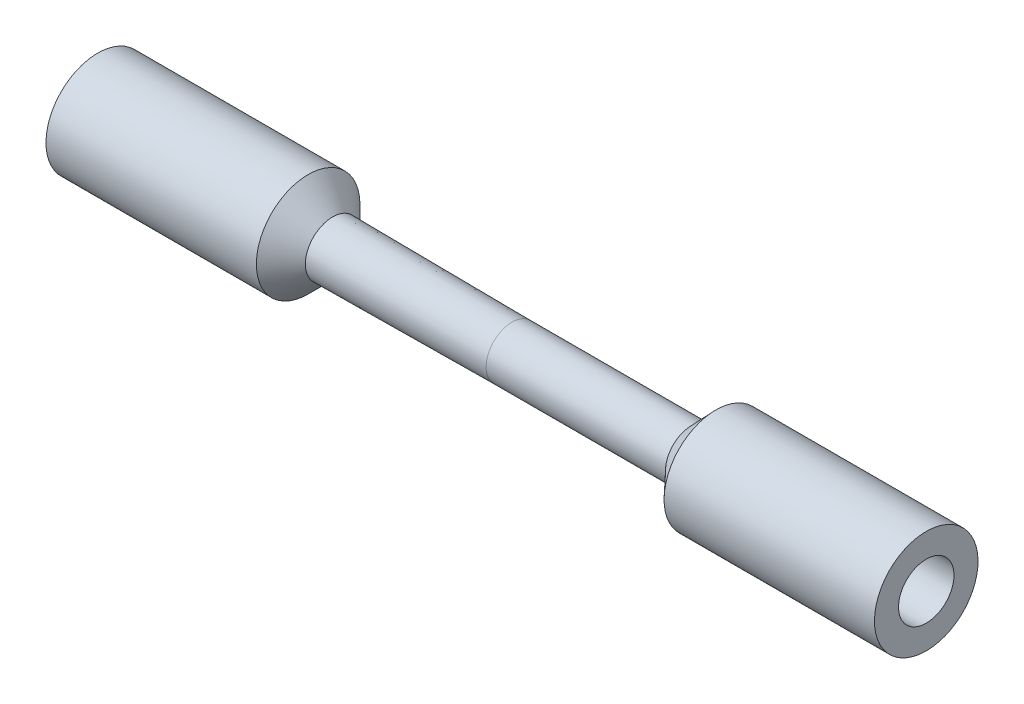
SolidWorks part; units mm, degrees
ref_plane "Front Plane" through (0, 0, 0) normal (0, 0, 1) x (1, 0, 0)
ref_plane "Top Plane" through (0, 0, 0) normal (0, 1, 0) x (1, 0, 0)
ref_plane "Right Plane" through (0, 0, 0) normal (1, 0, 0) x (0, 0, -1)
sketch "Sketch1" plane through (0, 0, 0) normal (0, 0, 1) x (1, 0, 0)
  line L0 (25.4, 1.5875) -> (14.4003, 1.5)
  line L1 (0, 0) -> (50.8, 0) construction
  line L2 (0, 0) -> (0, 3.175)
  line L3 (0, 3.175) -> (50.8, 3.175)
  line L4 (50.8, 0) -> (50.8, 3.175)
  line L5 (25.4, 3.175) -> (25.4, 0) construction
  line L6 (14.4003, 1.5) -> (12.9003, 0)
  line L7 (12.9003, 0) -> (0, 0)
  line L8 (37.8997, 0) -> (50.8, 0)
  line L9 (25.4, 1.5875) -> (36.4, 1.5875)
  line L10 (36.4, 1.5875) -> (37.8997, 0)
  point P208 (25.4, 1.5)
  dimension "D1" = 50.8
  dimension "D2" = 3.175
  dimension "D3" = 11
  dimension "D4" = 45
  dimension "D5" = 2.1213
revolve "Revolve1" add sketch "Sketch1" angle 360 about L3
sketch "Sketch4" plane through (0, 0, 0) normal (-1, 0, 0) x (0, 0, 1)
  point P0 (0, 3.175)
hole_wizard "M3 Clearance Hole1" positions "Sketch5" profile "Sketch6" hole size "M3" standard "ANSI Metric"
sketch "Sketch5" plane through (0, 0, 0) normal (-1, 0, 0) x (0, 0, 1)
  point P0 (0, 3.175)
sketch "Sketch6" plane through (0, 3.175, 0) normal (0, 1, 0) x (0, 0, 1)
  line L0 (0, 0) -> (0, 7.3715)
  line L1 (0, 7.3715) -> (1.7, 6.35)
  line L2 (1.7, 6.35) -> (1.7, 0)
  line L5 (1.7, 0) -> (0, 0)
  line L10 (0, 7.3715) -> (-1.7, 6.35) construction
  line L11 (0, -6.35) -> (0, 107.95) construction
  dimension "Hole Dia." = 3.4
  dimension "Hole Depth" = 6.35
  dimension "Drill Angle" = 118
ref_plane "Plane1" through (25.4, 0, 0) normal (-1, 0, 0) x (0, 0, 1)
mirror "Mirror1" about plane through (25.4, 0, 0) normal (-1, 0, 0) of "M3 Clearance Hole1"
equation "\"arm spacing\"= 2"
equation "\"D1@Sketch1\"=\"arm spacing\""
equation "\"D2@Sketch1\"=.25/2"
equation "\"symbol room\"= ( ( 35 / 2 ) - 6.5 )"
equation "\"D3@Sketch1\"=(\"symbol room\")/25.4"
